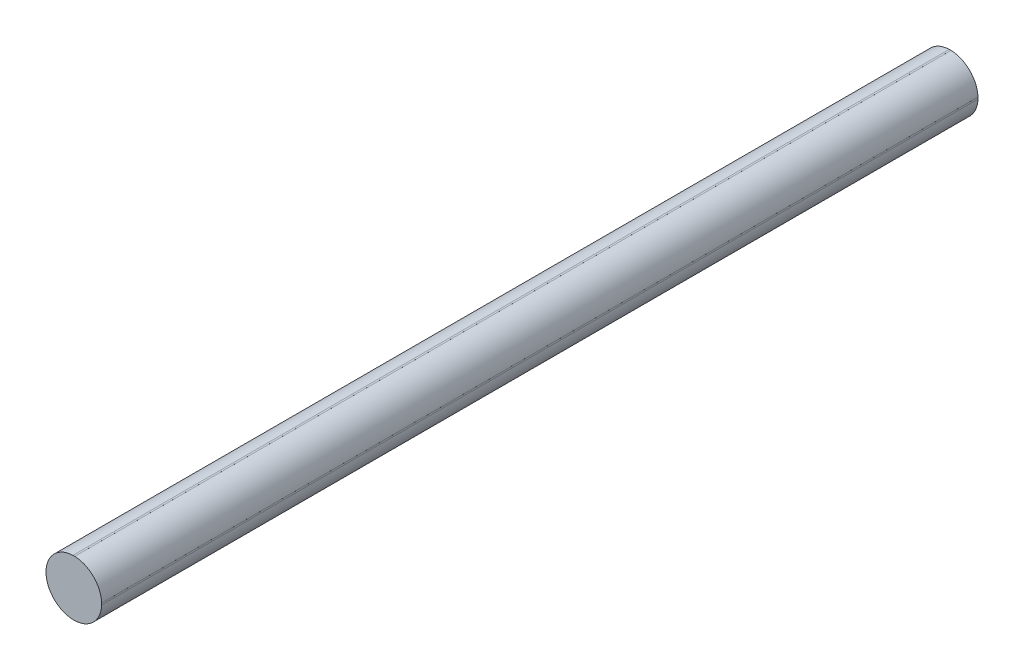
SolidWorks part; units mm, degrees
ref_plane "Alzado" through (0, 0, 0) normal (0, 0, 1) x (1, 0, 0)
ref_plane "Planta" through (0, 0, 0) normal (0, 1, 0) x (1, 0, 0)
ref_plane "Vista lateral" through (0, 0, 0) normal (1, 0, 0) x (0, 0, -1)
sketch "Croquis1" plane through (0, 0, 0) normal (0, 0, 1) x (1, 0, 0)
  circle A0 centre (0, 0) radius 31.75
  dimension "D1" = 63.5
extrude "Saliente-Extruir1" add sketch "Croquis1" along normal blind 1000
sketch "Croquis2" plane through (0, 0, 1000) normal (0, 0, 1) x (1, 0, 0)
  line L0 (31.75, 0) -> (31.75, -1)
  line L1 (31.75, -1) -> (30.75, -1)
  line L2 (30.75, -1) -> (30.75, 1)
  line L3 (30.75, 1) -> (31.75, 1)
  line L4 (31.75, 1) -> (31.75, 0)
  line L5 (0, 31.75) -> (0, 0) construction
  line L6 (-31.75, 1) -> (-31.75, 0)
  line L7 (-30.75, 1) -> (-31.75, 1)
  line L8 (-30.75, -1) -> (-30.75, 1)
  line L9 (-31.75, -1) -> (-30.75, -1)
  line L10 (-31.75, 0) -> (-31.75, -1)
  line L11 (0, 0) -> (-22.4506, 22.4506) construction
  line L12 (0, 31.75) -> (1, 31.75)
  line L13 (1, 31.75) -> (1, 30.75)
  line L14 (1, 30.75) -> (-1, 30.75)
  line L15 (-1, 30.75) -> (-1, 31.75)
  line L16 (-1, 31.75) -> (0, 31.75)
  line L17 (0, 0) -> (-19.1099, 0) construction
  line L18 (-1, -31.75) -> (0, -31.75)
  line L19 (-1, -30.75) -> (-1, -31.75)
  line L20 (1, -30.75) -> (-1, -30.75)
  line L21 (1, -31.75) -> (1, -30.75)
  line L22 (0, -31.75) -> (1, -31.75)
  circle A0 centre (0, 0) radius 31.75 construction
  dimension "D1" = 1
  dimension "D2" = 1
  dimension "D3" = 1
extrude "Saliente-Extruir2" add sketch "Croquis2" against normal up to surface (1000 mm away) up to face at (31.75, 0, 0)
